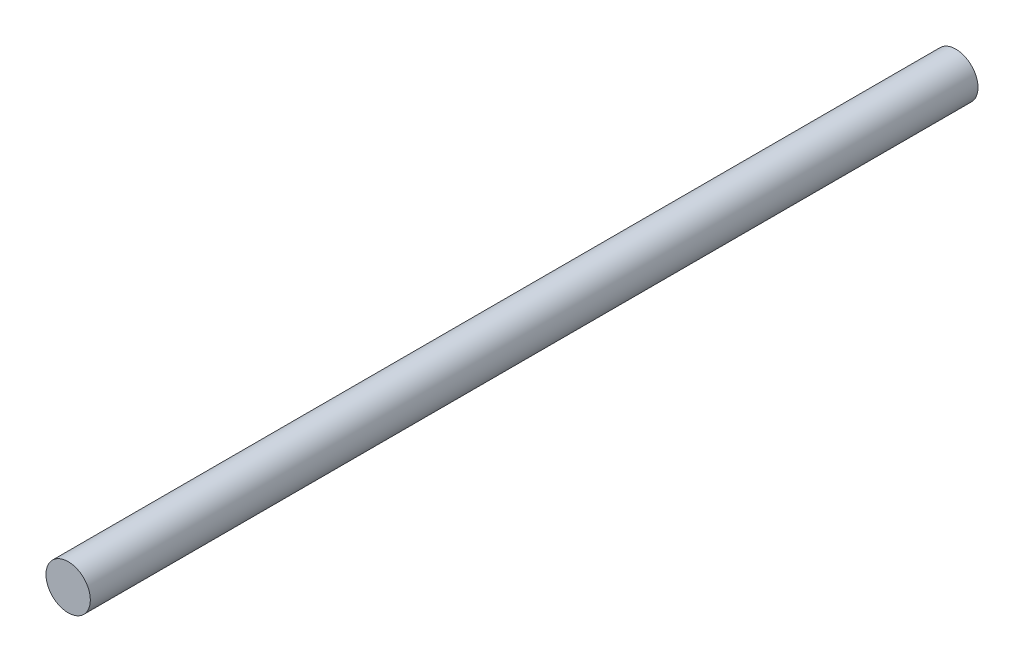
SolidWorks part; units mm, degrees
ref_plane "Plan de face" through (0, 0, 0) normal (0, 0, 1) x (1, 0, 0)
ref_plane "Plan de dessus" through (0, 0, 0) normal (0, 1, 0) x (1, 0, 0)
ref_plane "Plan de droite" through (0, 0, 0) normal (1, 0, 0) x (0, 0, -1)
sketch "Esquisse1" plane through (0, 0, 0) normal (0, 0, 1) x (1, 0, 0)
  circle A0 centre (0, 0) radius 4
  dimension "D1" = 8
extrude "Boss.-Extru.1" add sketch "Esquisse1" along normal blind 160
